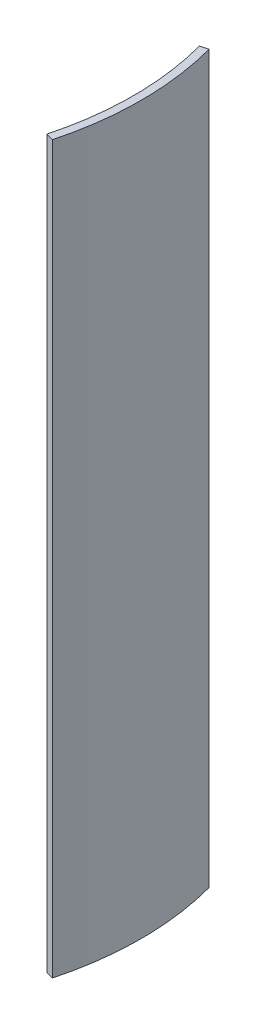
SolidWorks part; units mm, degrees
ref_plane "Front Plane" through (0, 0, 0) normal (0, 0, 1) x (1, 0, 0)
ref_plane "Top Plane" through (0, 0, 0) normal (0, 1, 0) x (1, 0, 0)
ref_plane "Right Plane" through (0, 0, 0) normal (1, 0, 0) x (0, 0, -1)
sketch "Sketch1" plane through (0, 0, 0) normal (0, 1, 0) x (1, 0, 0)
  line L0 (705.6088, 189.0673) -> (724.4444, 194.1143)
  line L1 (705.6088, -189.0673) -> (724.4444, -194.1143)
  arc A0 (705.6088, -189.0673) -> (705.6088, 189.0673) centre (0, 0) ccw
  arc A1 (724.4444, -194.1143) -> (724.4444, 194.1143) centre (0, 0) ccw
  point P6 (730.5, 0)
  point P7 (750, 0)
  dimension "D1" = 730.5
  dimension "D2" = 750
  dimension "D3" = 705.6088
extrude "Boss-Extrude1" add sketch "Sketch1" along normal blind 1800
